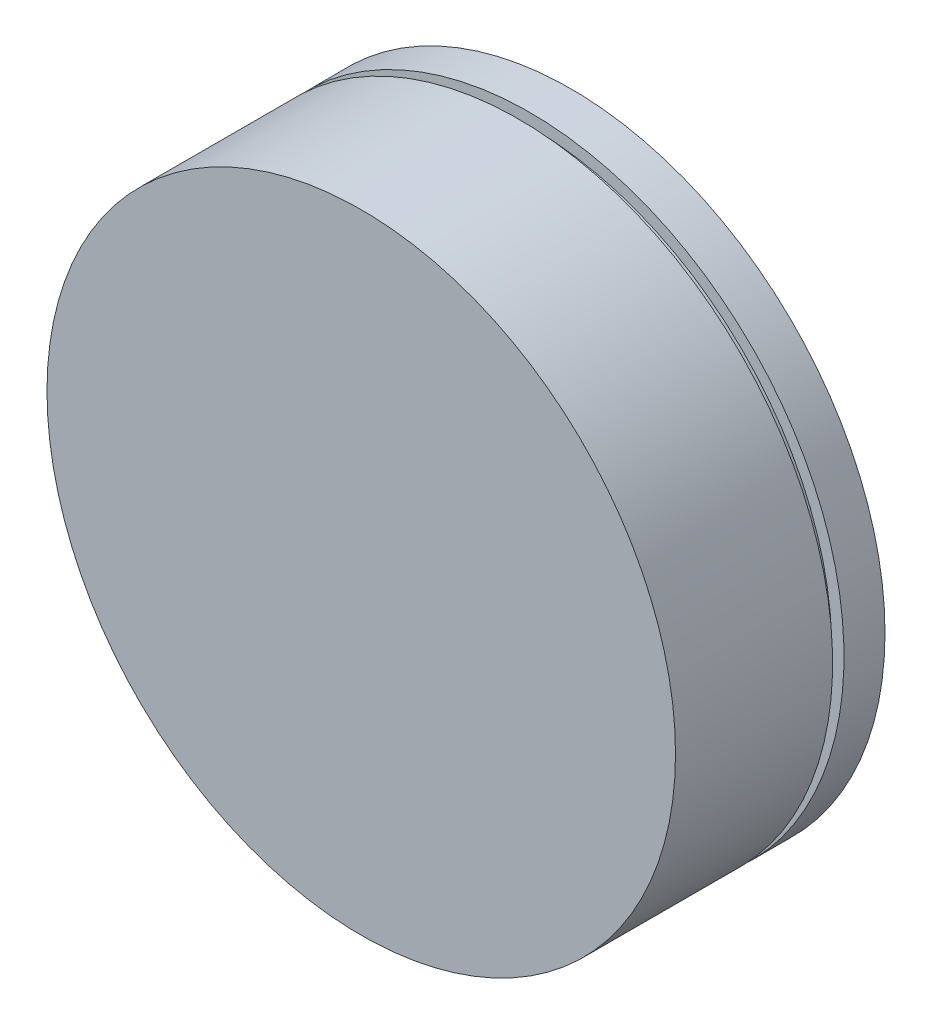
SolidWorks part; units mm, degrees
ref_plane "Front Plane" through (0, 0, 0) normal (0, 0, 1) x (1, 0, 0)
ref_plane "Top Plane" through (0, 0, 0) normal (0, 1, 0) x (1, 0, 0)
ref_plane "Right Plane" through (0, 0, 0) normal (1, 0, 0) x (0, 0, -1)
sketch "Sketch1" plane through (0, 0, 0) normal (0, 0, 1) x (1, 0, 0)
  circle A0 centre (0, 0) radius 38.1
  dimension "D1" = 76.2
extrude "Boss-Extrude1" add sketch "Sketch1" along normal blind 25.4
sketch "Sketch2" plane through (0, 0, 0) normal (0, 1, 0) x (1, 0, 0)
  line L0 (-38.1, -4.9718) -> (-36.6234, -4.9718)
  line L1 (-38.1, 0) -> (-38.1, -25.4) construction
  line L2 (-36.6234, -4.9718) -> (-36.6234, -6.35)
  line L3 (-36.6234, -6.35) -> (-38.1, -6.35)
  line L4 (-38.1, -25.4) -> (38.1, -25.4) construction
  line L5 (-38.1, -6.35) -> (-38.1, -4.9718)
  line L6 (0, 0) -> (0, -29.3332) construction
  dimension "D1" = 19.05
revolve "Cut-Revolve1" cut sketch "Sketch2" angle 360 about L6
